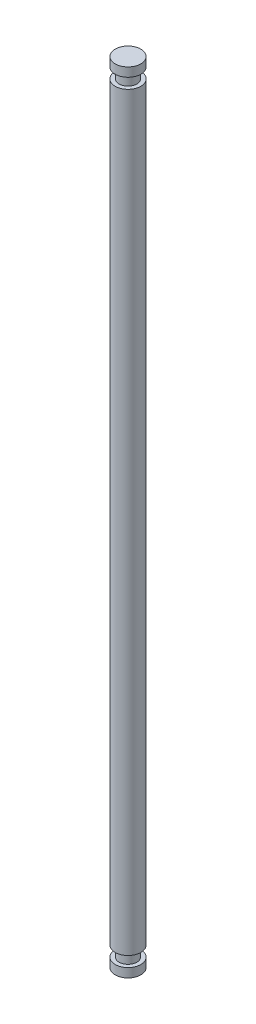
SolidWorks part; units mm, degrees
ref_plane "Front Plane" through (0, 0, 0) normal (1, 0, 0) x (0, 1, 0)
ref_plane "Top Plane" through (0, 0, 0) normal (0, 0, 1) x (0, 1, 0)
ref_plane "Right Plane" through (0, 0, 0) normal (0, 1, 0) x (-1, 0, 0)
sketch "Sketch1" plane through (0, 0, 0) normal (0, 0, 1) x (0, 1, 0)
  line L0 (-976.376, 0) -> (-976.376, 31.7309)
  line L1 (-976.376, 31.7309) -> (-954.024, 31.7309)
  line L2 (-954.024, 31.7309) -> (-954.024, 22.0218)
  line L3 (-954.024, 22.0218) -> (-928.2176, 22.0218)
  line L4 (-928.2176, 22.0218) -> (-928.2176, 31.7309)
  line L5 (-928.2176, 31.7309) -> (928.3446, 31.7309)
  line L6 (928.3446, 31.7309) -> (928.3446, 22.0218)
  line L7 (928.3446, 22.0218) -> (954.151, 22.0218)
  line L8 (954.151, 22.0218) -> (954.151, 31.7309)
  line L9 (954.151, 31.7309) -> (976.376, 31.7309)
  line L10 (976.376, 31.7309) -> (976.376, 0)
  line L11 (976.376, 0) -> (-976.376, 0)
  line L12 (-1001.776, 0) -> (1001.776, 0) construction
  dimension "D1" = 22.225
  dimension "D2" = 48.0314
  dimension "D3" = 1904.5936
  dimension "D4" = 1930.4
  dimension "D5" = 1952.752
  dimension "D6" = 9.7092
  dimension "D7" = 31.7309
revolve "Revolve1" add sketch "Sketch1" angle 360 about L12
sketch "Sketch2" plane through (0, 0, 0) normal (0, 1, 0) x (-1, 0, 0)
  line L1 (24.6062, -6.35) -> (88.0682, -6.35)
  line L2 (24.6062, -6.35) -> (24.6062, 6.35)
  line L3 (24.6062, 6.35) -> (88.0682, 6.35)
  line L4 (88.0682, -6.35) -> (88.0682, 6.35)
  dimension "D1" = 63.4619
  dimension "D2" = 12.7
extrude "Cut-Extrude2" cut sketch "Sketch2" along normal blind 1856.5622 from offset 928.2176
